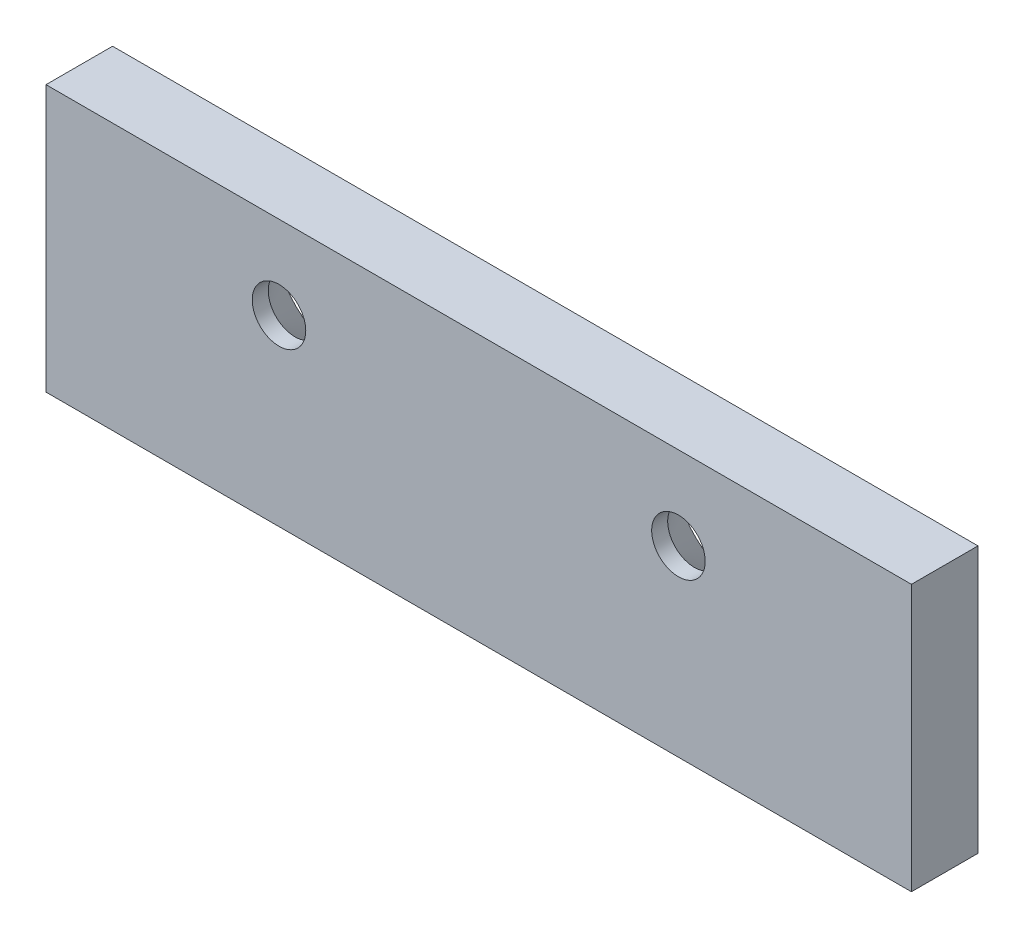
SolidWorks part; units mm, degrees
material "6061 Alloy"
ref_plane "Front Plane" through (0, 0, 0) normal (0, 0, 1) x (1, 0, 0)
ref_plane "Top Plane" through (0, 0, 0) normal (0, 1, 0) x (1, 0, 0)
ref_plane "Right Plane" through (0, 0, 0) normal (1, 0, 0) x (0, 0, -1)
sketch "Sketch1" plane through (0, 0, 0) normal (0, 0, 1) x (1, 0, 0)
  line L1 (0, 0) -> (82.55, 0)
  line L2 (0, 0) -> (0, 25.4)
  line L3 (0, 25.4) -> (82.55, 25.4)
  line L4 (82.55, 0) -> (82.55, 25.4)
  dimension "D1" = 82.55
  dimension "D2" = 25.4
extrude "Boss-Extrude1" add sketch "Sketch1" against normal blind 6.35
hole_wizard "1/4-20 Tapped Hole1" positions "Sketch2" profile "Sketch3" tap size "1/4-20" standard "ANSI Inch" end condition through all
sketch "Sketch2" plane through (0, 0, 0) normal (0, 0, 1) x (1, 0, 0)
  line L0 (82.55, 25.4) -> (0, 25.4) construction
  line L1 (0, 25.4) -> (0, 0) construction
  line L2 (82.55, 0) -> (82.55, 25.4) construction
  point P0 (22.225, 17.4625)
  point P2 (60.325, 17.4625)
  dimension "D1" = 7.9375
  dimension "D2" = 7.9375
  dimension "D3" = 22.225
  dimension "D4" = 22.225
cosmetic thread "Hole Thread1"
cosmetic thread "Hole Thread2"
sketch "Sketch3" plane through (22.225, 17.4625, 0) normal (1, 0, 0) x (0, -1, 0)
  line L0 (0, 0) -> (0, 6.35)
  line L1 (0, 6.35) -> (6.7437, 6.35)
  line L2 (2.5527, 1.5288) -> (2.5527, 0)
  line L5 (2.5527, 0) -> (0, 0)
  line L7 (6.7437, 6.35) -> (2.5527, 1.5288)
  line L8 (-6.7437, 6.35) -> (-2.5527, 1.5288) construction
  line L11 (0, -6.35) -> (0, 107.95) construction
  dimension "Thru Tap Drill Dia." = 5.1054
  dimension "Thru Tap Drill Depth" = 6.35
  dimension "Far C'Sink Dia." = 13.4874
  dimension "Far C'Sink Angle" = 82
